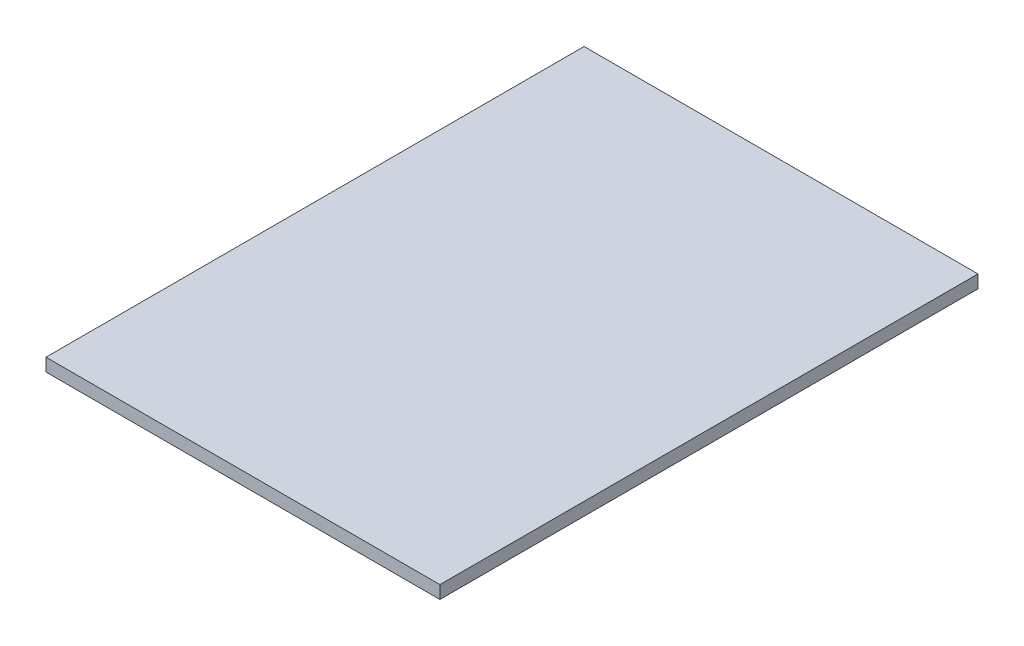
SolidWorks part; units mm, degrees
ref_plane "Front" through (0, 0, 0) normal (0, 0, 1) x (1, 0, 0)
ref_plane "Top" through (0, 0, 0) normal (0, 1, 0) x (1, 0, 0)
ref_plane "Right" through (0, 0, 0) normal (1, 0, 0) x (0, 0, -1)
sketch "Sketch2" plane through (0, 0, 0) normal (0, 1, 0) x (1, 0, 0)
  line L9 (0, 0) -> (122.1, 0)
  line L10 (0, 0) -> (0, 192.8)
  line L11 (0, 192.8) -> (122.1, 192.8)
  line L12 (122.1, 0) -> (122.1, 192.8)
  dimension "D3" = 122.1
  dimension "D4" = 192.8
extrude "Boss-Extrude3" add sketch "Sketch2" along normal blind 4 contours L11 L12 L9 L10
sketch "Sketch3" plane through (0, 0, -192.8) normal (0, 0, -1) x (-1, 0, 0)
  line L0 (0, 0) -> (-122.1, 0) construction
  line L1 (0, 4) -> (-122.1, 4)
  line L2 (0, 4) -> (0, 0)
  line L3 (0, 0) -> (-122.1, 0)
  line L4 (-122.1, 4) -> (-122.1, 0)
extrude "Boss-Extrude4" add sketch "Sketch3" along normal blind 5
sketch "Sketch4" plane through (0, 0, -197.8) normal (0, 0, -1) x (-1, 0, 0)
  line L1 (29.8865, -62.252) -> (-184.0913, -62.252)
  line L2 (29.8865, -62.252) -> (29.8865, 74.8729)
  line L3 (29.8865, 74.8729) -> (-184.0913, 74.8729)
  line L4 (-184.0913, -62.252) -> (-184.0913, 74.8729)
extrude "Cut-Extrude1" cut sketch "Sketch4" against normal blind 12
sketch "Sketch5" plane through (0, 0, 0) normal (0, 0, 1) x (1, 0, 0)
  line L1 (-34.3944, 76.5721) -> (161.9783, 76.5721)
  line L2 (-34.3944, 76.5721) -> (-34.3944, -59.194)
  line L3 (-34.3944, -59.194) -> (161.9783, -59.194)
  line L4 (161.9783, 76.5721) -> (161.9783, -59.194)
extrude "Cut-Extrude2" cut sketch "Sketch5" against normal blind 19
